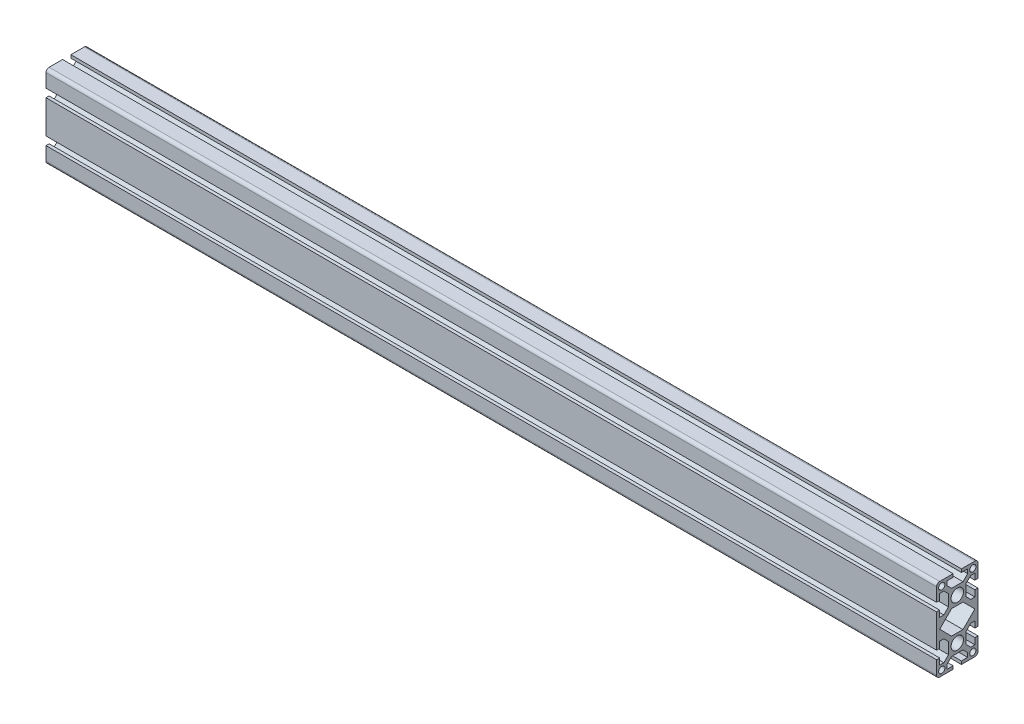
SolidWorks part; units mm, degrees
ref_plane "Front Plane" through (0, 0, 0) normal (0, 0, 1) x (1, 0, 0)
ref_plane "Top Plane" through (0, 0, 0) normal (0, 1, 0) x (1, 0, 0)
ref_plane "Right Plane" through (0, 0, 0) normal (1, 0, 0) x (0, 0, -1)
sketch "Sketch1" plane through (0, 0, 0) normal (1, 0, 0) x (0, 0, -1)
  line L0 (-20, -4) -> (-17, -4)
  line L1 (20, 0) -> (-20, 0) construction
  line L2 (0, 60) -> (0, -20) construction
  line L3 (-4, -20) -> (-17, -20)
  line L4 (-20, -4) -> (-20, -17)
  line L5 (-17, -4) -> (-17, -10)
  line L6 (-17, -10) -> (-13, -10)
  line L7 (-13, -10) -> (-8.5, -5.5)
  line L8 (-8.5, -5.5) -> (-8.5, 5.5)
  line L9 (-20, -20) -> (0, 0) construction
  line L10 (-5.5, -8.5) -> (5.5, -8.5)
  line L11 (-10, -13) -> (-5.5, -8.5)
  line L12 (-10, -17) -> (-10, -13)
  line L13 (-4, -17) -> (-10, -17)
  line L14 (-4, -20) -> (-4, -17)
  line L15 (-20, 20) -> (0, 0) construction
  line L16 (-20, 20) -> (20, 20) construction
  line L17 (-5.5, 8.5) -> (-17, 20)
  line L18 (5.5, 8.5) -> (17, 20)
  line L19 (20, 60) -> (0, 40) construction
  line L20 (-20, 60) -> (0, 40) construction
  line L21 (-5.5, 8.5) -> (5.5, 8.5)
  line L22 (-13, 10) -> (-8.5, 5.5)
  line L23 (-17, 10) -> (-13, 10)
  line L24 (-17, 4) -> (-17, 10)
  line L25 (-20, 4) -> (-20, 36)
  line L26 (-20, 4) -> (-17, 4)
  line L27 (20, 20) -> (0, 0) construction
  line L28 (20, -20) -> (0, 0) construction
  line L29 (20, 4) -> (17, 4)
  line L30 (4, 60) -> (4, 57)
  line L31 (20, 4) -> (20, 20)
  line L32 (17, 4) -> (17, 10)
  line L33 (17, 10) -> (13, 10)
  line L34 (13, 10) -> (8.5, 5.5)
  line L35 (4, 60) -> (17, 60)
  line L36 (-4, 60) -> (-4, 57)
  line L37 (-4, 60) -> (-17, 60)
  line L38 (20, 20) -> (0, 40) construction
  line L39 (4, -20) -> (17, -20)
  line L40 (4, -20) -> (4, -17)
  line L41 (4, -17) -> (10, -17)
  line L42 (10, -17) -> (10, -13)
  line L43 (10, -13) -> (5.5, -8.5)
  line L44 (8.5, -5.5) -> (8.5, 5.5)
  line L45 (13, -10) -> (8.5, -5.5)
  line L46 (17, -10) -> (13, -10)
  line L47 (17, -4) -> (17, -10)
  line L48 (20, -4) -> (20, -17)
  line L49 (20, -4) -> (17, -4)
  line L50 (-20, 20) -> (0, 40) construction
  line L51 (20, 40) -> (-20, 40) construction
  line L52 (20, 44) -> (17, 44)
  line L53 (20, 44) -> (20, 57)
  line L54 (17, 44) -> (17, 50)
  line L55 (17, 50) -> (13, 50)
  line L56 (13, 50) -> (8.5, 45.5)
  line L57 (8.5, 45.5) -> (8.5, 34.5)
  line L58 (10, 53) -> (5.5, 48.5)
  line L59 (10, 57) -> (10, 53)
  line L60 (4, 57) -> (10, 57)
  line L61 (13, 30) -> (8.5, 34.5)
  line L62 (17, 30) -> (13, 30)
  line L63 (17, 36) -> (17, 30)
  line L64 (20, 36) -> (20, 20)
  line L65 (20, 36) -> (17, 36)
  line L66 (-20, 36) -> (-17, 36)
  line L67 (-17, 36) -> (-17, 30)
  line L68 (-17, 30) -> (-13, 30)
  line L69 (-13, 30) -> (-8.5, 34.5)
  line L70 (-5.5, 31.5) -> (5.5, 31.5)
  line L71 (5.5, 31.5) -> (17, 20)
  line L72 (-5.5, 31.5) -> (-17, 20)
  line L73 (-4, 57) -> (-10, 57)
  line L74 (-10, 57) -> (-10, 53)
  line L75 (-10, 53) -> (-5.5, 48.5)
  line L76 (-5.5, 48.5) -> (5.5, 48.5)
  line L77 (-8.5, 45.5) -> (-8.5, 34.5)
  line L78 (-13, 50) -> (-8.5, 45.5)
  line L79 (-17, 50) -> (-13, 50)
  line L80 (-17, 44) -> (-17, 50)
  line L81 (-20, 44) -> (-20, 57)
  line L82 (-20, 44) -> (-17, 44)
  circle A0 centre (0, 0) radius 6
  circle A1 centre (-15, -15) radius 3
  arc A2 (-17, -20) -> (-20, -17) centre (-17, -17) cw
  arc A3 (17, 60) -> (20, 57) centre (17, 57) cw
  arc A4 (-17, 60) -> (-20, 57) centre (-17, 57) ccw
  circle A5 centre (15, 55) radius 3
  circle A6 centre (-15, 55) radius 3
  arc A7 (17, -20) -> (20, -17) centre (17, -17) ccw
  circle A8 centre (15, -15) radius 3
  circle A9 centre (0, 40) radius 6
  point P4 (0, 0)
  point P33 (0, 20)
  point P37 (-8.5, 0)
  point P60 (0, 8.5)
  point P68 (0, -8.5)
  point P73 (8.5, 0)
  point P110 (8.5, 40)
  point P111 (0, 48.5)
  point P112 (0, 31.5)
  point P113 (-8.5, 40)
  point P114 (0, 0)
  point P115 (1.9584, 1.0547)
  point P116 (0, 0)
  point P118 (0, 0)
  point P120 (0, 0)
  point P123 (0, 0)
  dimension "D1" = 12
  dimension "D4" = 3
  dimension "D5" = 6
  dimension "D2" = 20
  dimension "D3" = 20
  dimension "D6" = 5
  dimension "D7" = 5
  dimension "D8" = 3
  dimension "D9" = 10
  dimension "D10" = 8.5
  dimension "D11" = 45
  dimension "D12" = 16
  dimension "D13" = 4
  dimension "D14" = 45
extrude "Boss-Extrude1" add sketch "Sketch1" along normal blind 860 contours L39 A7 L48 L49 L47 L46 L45 L44 L34 L33 L32 L29 L31 L64 L65 L63 L62 L61 L57 L56 L55 L54 L52 L53 A3 L35 L30 L60 L59 L58 L76 L75 L74 L73 L36 L37 A4 L81 L82 L80 L79 L78 L77 L69 L68 L67 L66 L25 L26 L24 L23
